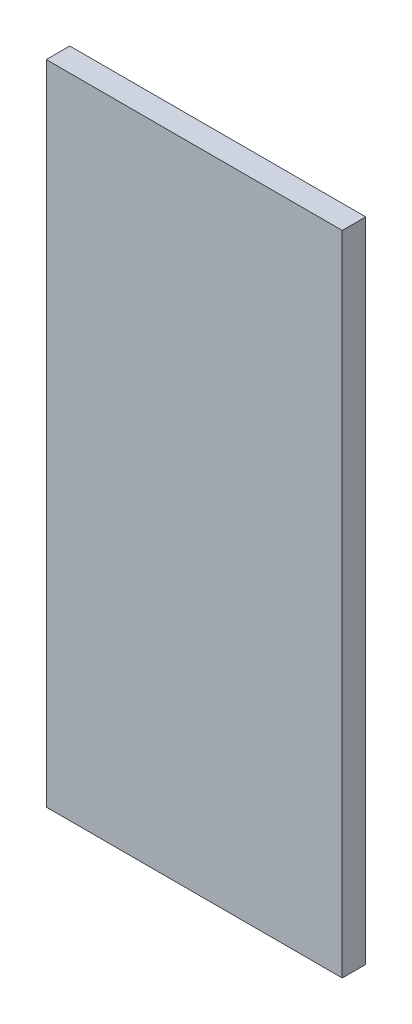
SolidWorks part; units mm, degrees
material "Aleación 1060"
ref_plane "Alzado" through (0, 0, 0) normal (0, 0, 1) x (1, 0, 0)
ref_plane "Planta" through (0, 0, 0) normal (0, 1, 0) x (1, 0, 0)
ref_plane "Vista lateral" through (0, 0, 0) normal (1, 0, 0) x (0, 0, -1)
sketch "Croquis1" plane through (0, 0, 0) normal (0, 0, 1) x (1, 0, 0)
  line L1 (-80, -175) -> (80, -175)
  line L2 (-80, -175) -> (-80, 175)
  line L3 (-80, 175) -> (80, 175)
  line L4 (80, -175) -> (80, 175)
  line L5 (-80, -175) -> (80, 175) construction
  line L6 (-80, 175) -> (80, -175) construction
  point P0 (0, 0)
  dimension "D1" = 350
  dimension "D2" = 160
extrude "Saliente-Extruir1" add sketch "Croquis1" along normal blind 12.7
